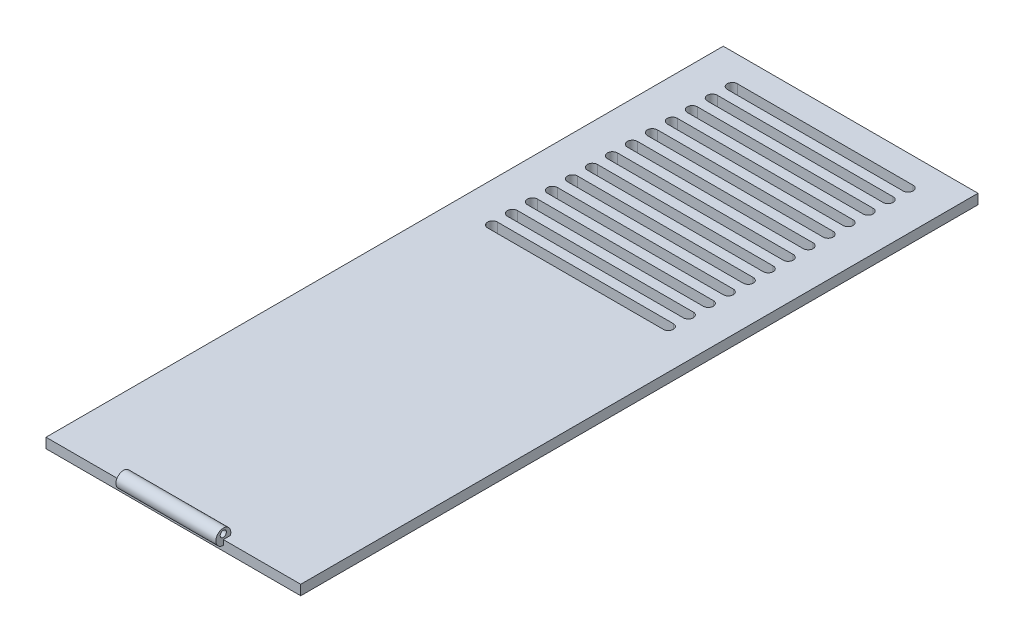
SolidWorks part; units mm, degrees
ref_plane "Front Plane" through (0, 0, 0) normal (0, 0, 1) x (1, 0, 0)
ref_plane "Top Plane" through (0, 0, 0) normal (0, 1, 0) x (1, 0, 0)
ref_plane "Right Plane" through (0, 0, 0) normal (1, 0, 0) x (0, 0, -1)
sketch "Sketch1" plane through (0, 0, 0) normal (0, 1, 0) x (1, 0, 0)
  line L1 (-56, 63.4545) -> (-5, 63.4545)
  line L2 (-56, 63.4545) -> (-56, -72.5455)
  line L3 (-56, -72.5455) -> (-5, -72.5455)
  line L4 (-5, 63.4545) -> (-5, -72.5455)
  dimension "D1" = 136
  dimension "D2" = 51
extrude "Boss-Extrude1" add sketch "Sketch1" along normal blind 2
sketch "Sketch3" plane through (0, 2, 0) normal (0, 1, 0) x (1, 0, 0)
  line L0 (-5, 63.4545) -> (-56, 63.4545) construction
  line L1 (-49.1, 58.3545) -> (-11.9, 58.3545)
  line L2 (-49.1, 58.3545) -> (-49.1, 8.4545)
  line L3 (-49.1, 8.4545) -> (-11.9, 8.4545)
  line L4 (-11.9, 58.3545) -> (-11.9, 8.4545)
  dimension "D1" = 5.1
  dimension "D2" = 37.2
  dimension "D4" = 49.9
sketch "Sketch4" plane through (0, 2, 0) normal (0, 1, 0) x (1, 0, 0)
  line L0 (-48.1, 57.3545) -> (-12.9, 57.3545) construction
  line L1 (-48.1, 58.3545) -> (-12.9, 58.3545)
  line L2 (-48.1, 56.3545) -> (-12.9, 56.3545)
  line L3 (-49.1, 58.3545) -> (-49.1, 8.4545) construction
  line L4 (-49.1, 58.3545) -> (-11.9, 58.3545) construction
  line L5 (-48.1, 53.3545) -> (-12.9, 53.3545) construction
  line L6 (-48.1, 54.3545) -> (-12.9, 54.3545)
  line L7 (-48.1, 52.3545) -> (-12.9, 52.3545)
  line L8 (-48.1, 49.3545) -> (-12.9, 49.3545) construction
  line L9 (-48.1, 50.3545) -> (-12.9, 50.3545)
  line L10 (-48.1, 48.3545) -> (-12.9, 48.3545)
  line L11 (-48.1, 45.3545) -> (-12.9, 45.3545) construction
  line L12 (-48.1, 46.3545) -> (-12.9, 46.3545)
  line L13 (-48.1, 44.3545) -> (-12.9, 44.3545)
  line L14 (-48.1, 41.3545) -> (-12.9, 41.3545) construction
  line L15 (-48.1, 42.3545) -> (-12.9, 42.3545)
  line L16 (-48.1, 40.3545) -> (-12.9, 40.3545)
  line L17 (-48.1, 37.3545) -> (-12.9, 37.3545) construction
  line L18 (-48.1, 38.3545) -> (-12.9, 38.3545)
  line L19 (-48.1, 36.3545) -> (-12.9, 36.3545)
  line L20 (-48.1, 33.3545) -> (-12.9, 33.3545) construction
  line L21 (-48.1, 34.3545) -> (-12.9, 34.3545)
  line L22 (-48.1, 32.3545) -> (-12.9, 32.3545)
  line L23 (-48.1, 29.3545) -> (-12.9, 29.3545) construction
  line L24 (-48.1, 30.3545) -> (-12.9, 30.3545)
  line L25 (-48.1, 28.3545) -> (-12.9, 28.3545)
  line L26 (-48.1, 25.3545) -> (-12.9, 25.3545) construction
  line L27 (-48.1, 26.3545) -> (-12.9, 26.3545)
  line L28 (-48.1, 24.3545) -> (-12.9, 24.3545)
  line L29 (-48.1, 21.3545) -> (-12.9, 21.3545) construction
  line L30 (-48.1, 22.3545) -> (-12.9, 22.3545)
  line L31 (-48.1, 20.3545) -> (-12.9, 20.3545)
  line L32 (-48.1, 17.3545) -> (-12.9, 17.3545) construction
  line L33 (-48.1, 18.3545) -> (-12.9, 18.3545)
  line L34 (-48.1, 16.3545) -> (-12.9, 16.3545)
  line L35 (-48.1, 13.3545) -> (-12.9, 13.3545) construction
  line L36 (-48.1, 14.3545) -> (-12.9, 14.3545)
  line L37 (-48.1, 12.3545) -> (-12.9, 12.3545)
  line L38 (-48.1, 9.3545) -> (-12.9, 9.3545) construction
  line L39 (-48.1, 10.3545) -> (-12.9, 10.3545)
  line L40 (-48.1, 8.3545) -> (-12.9, 8.3545)
  arc A0 (-48.1, 58.3545) -> (-48.1, 56.3545) centre (-48.1, 57.3545) ccw
  arc A1 (-12.9, 56.3545) -> (-12.9, 58.3545) centre (-12.9, 57.3545) ccw
  arc A2 (-48.1, 54.3545) -> (-48.1, 52.3545) centre (-48.1, 53.3545) ccw
  arc A3 (-12.9, 52.3545) -> (-12.9, 54.3545) centre (-12.9, 53.3545) ccw
  arc A4 (-48.1, 50.3545) -> (-48.1, 48.3545) centre (-48.1, 49.3545) ccw
  arc A5 (-12.9, 48.3545) -> (-12.9, 50.3545) centre (-12.9, 49.3545) ccw
  arc A6 (-48.1, 46.3545) -> (-48.1, 44.3545) centre (-48.1, 45.3545) ccw
  arc A7 (-12.9, 44.3545) -> (-12.9, 46.3545) centre (-12.9, 45.3545) ccw
  arc A8 (-48.1, 42.3545) -> (-48.1, 40.3545) centre (-48.1, 41.3545) ccw
  arc A9 (-12.9, 40.3545) -> (-12.9, 42.3545) centre (-12.9, 41.3545) ccw
  arc A10 (-48.1, 38.3545) -> (-48.1, 36.3545) centre (-48.1, 37.3545) ccw
  arc A11 (-12.9, 36.3545) -> (-12.9, 38.3545) centre (-12.9, 37.3545) ccw
  arc A12 (-48.1, 34.3545) -> (-48.1, 32.3545) centre (-48.1, 33.3545) ccw
  arc A13 (-12.9, 32.3545) -> (-12.9, 34.3545) centre (-12.9, 33.3545) ccw
  arc A14 (-48.1, 30.3545) -> (-48.1, 28.3545) centre (-48.1, 29.3545) ccw
  arc A15 (-12.9, 28.3545) -> (-12.9, 30.3545) centre (-12.9, 29.3545) ccw
  arc A16 (-48.1, 26.3545) -> (-48.1, 24.3545) centre (-48.1, 25.3545) ccw
  arc A17 (-12.9, 24.3545) -> (-12.9, 26.3545) centre (-12.9, 25.3545) ccw
  arc A18 (-48.1, 22.3545) -> (-48.1, 20.3545) centre (-48.1, 21.3545) ccw
  arc A19 (-12.9, 20.3545) -> (-12.9, 22.3545) centre (-12.9, 21.3545) ccw
  arc A20 (-48.1, 18.3545) -> (-48.1, 16.3545) centre (-48.1, 17.3545) ccw
  arc A21 (-12.9, 16.3545) -> (-12.9, 18.3545) centre (-12.9, 17.3545) ccw
  arc A22 (-48.1, 14.3545) -> (-48.1, 12.3545) centre (-48.1, 13.3545) ccw
  arc A23 (-12.9, 12.3545) -> (-12.9, 14.3545) centre (-12.9, 13.3545) ccw
  arc A24 (-48.1, 10.3545) -> (-48.1, 8.3545) centre (-48.1, 9.3545) ccw
  arc A25 (-12.9, 8.3545) -> (-12.9, 10.3545) centre (-12.9, 9.3545) ccw
  point P2 (-30.5, 57.3545)
  point P7 (-49.1, 57.3545)
  point P16 (-30.5, 53.3545)
  point P23 (-30.5, 49.3545)
  point P30 (-30.5, 45.3545)
  point P37 (-30.5, 41.3545)
  point P44 (-30.5, 37.3545)
  point P51 (-30.5, 33.3545)
  point P58 (-30.5, 29.3545)
  point P65 (-30.5, 25.3545)
  point P72 (-30.5, 21.3545)
  point P79 (-30.5, 17.3545)
  point P86 (-30.5, 13.3545)
  point P93 (-30.5, 9.3545)
  dimension "D1" = 0
  dimension "D3" = 13
  dimension "D2" = 0
extrude "Cut-Extrude1" cut sketch "Sketch4" against normal blind 10
sketch "Sketch5" plane through (0, 0, -63.4545) normal (0, 0, -1) x (-1, 0, 0)
  line L1 (56, 2) -> (57, 2)
  line L2 (56, 2) -> (56, 0)
  line L3 (56, 0) -> (57, 0)
  line L4 (57, 2) -> (57, 0)
  line L5 (5, 2) -> (4, 2)
  line L6 (5, 2) -> (5, 0)
  line L7 (5, 0) -> (4, 0)
  line L8 (4, 2) -> (4, 0)
  point P10 (57, 1)
  dimension "D1" = 1
  dimension "D2" = 1
extrude "Boss-Extrude2" add sketch "Sketch5" against normal up to surface (136 mm away) up to face at (-30.5, 1, 72.5455)
sketch "Sketch6" plane through (0, 0, -63.4545) normal (0, 0, -1) x (-1, 0, 0)
  line L1 (57, 0) -> (58, 0)
  line L2 (57, 0) -> (57, 2)
  line L3 (57, 2) -> (58, 2)
  line L4 (58, 0) -> (58, 2)
  line L5 (4, 0) -> (3, 0)
  line L6 (4, 0) -> (4, 2)
  line L7 (4, 2) -> (3, 2)
  line L8 (3, 0) -> (3, 2)
  dimension "D1" = 1
  dimension "D2" = 1
extrude "Boss-Extrude3" add sketch "Sketch6" against normal up to surface (136 mm away) up to face at (-30.5, 1, 72.5455)
sketch "Sketch7" plane through (0, 0, 72.5455) normal (0, 0, 1) x (1, 0, 0)
  line L1 (-66.7377, 9.812) -> (2.0582, 9.812)
  line L2 (-66.7377, 9.812) -> (-66.7377, -16.6136)
  line L3 (-66.7377, -16.6136) -> (2.0582, -16.6136)
  line L4 (2.0582, 9.812) -> (2.0582, -16.6136)
extrude "Cut-Extrude2" cut sketch "Sketch7" against normal blind 0.4
sketch "Sketch8" plane through (0, 0, -63.4545) normal (0, 0, -1) x (-1, 0, 0)
  line L0 (3, 0) -> (58, 0) construction
  line L1 (3, 2) -> (5, 2)
  line L2 (3, 2) -> (3, 0)
  line L3 (3, 0) -> (5, 0)
  line L4 (5, 2) -> (5, 0)
  line L6 (58, 2) -> (56, 2)
  line L7 (58, 2) -> (58, 0)
  line L8 (58, 0) -> (56, 0)
  line L9 (56, 2) -> (56, 0)
  dimension "D1" = 2
  dimension "D2" = 2
extrude "Cut-Extrude3" cut sketch "Sketch8" against normal blind 135.6
sketch "Sketch9" plane through (-56, 0, 0) normal (-1, 0, 0) x (0, 0, 1)
  line L1 (72.1455, 2) -> (72.1455, 0) construction
  circle A0 centre (72.1455, 2.5) radius 1.5
  point P6 (0, 0)
ref_plane "Plane1" through (-30.5, 0, 0) normal (-1, 0, 0) x (0, 0, 1)
sketch "Sketch11" plane through (-30.5, 0, 0) normal (-1, 0, 0) x (0, 0, 1)
  circle A0 centre (72.1455, 2.5) radius 1.5
extrude "Boss-Extrude6" add sketch "Sketch11" along normal blind 10 and the other way blind 10
sketch "Sketch14" plane through (-40.5, 0, 0) normal (-1, 0, 0) x (0, 0, 1)
  line L0 (72.1455, 4) -> (72.1455, 2) construction
  arc A0 (72.1455, 1) -> (70.7312, 2) centre (72.1455, 2.5) ccw construction
  circle A1 centre (72.1455, 3) radius 0.62
extrude "Cut-Extrude5" cut sketch "Sketch14" against normal up to surface (20 mm away) up to face at (-20.5, 2.4082, 72.1984)
